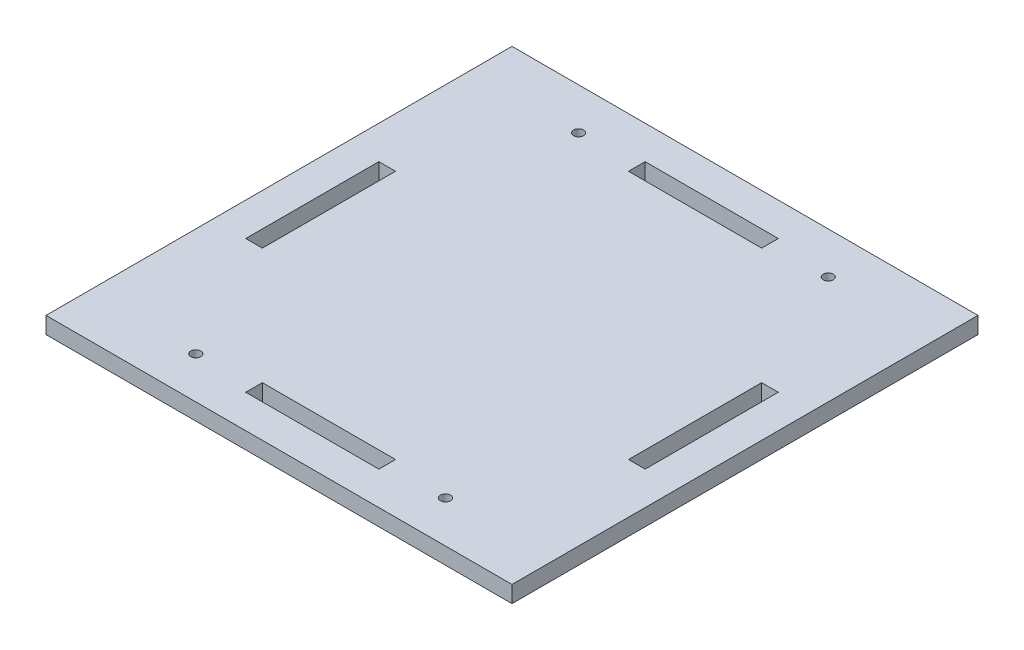
SolidWorks part; units mm, degrees
material "CA"
ref_plane "Alzado" through (0, 0, 0) normal (0, 0, 1) x (1, 0, 0)
ref_plane "Planta" through (0, 0, 0) normal (0, 1, 0) x (1, 0, 0)
ref_plane "Vista lateral" through (0, 0, 0) normal (1, 0, 0) x (0, 0, -1)
sketch "Croquis2" plane through (0, 0, 0) normal (0, 1, 0) x (1, 0, 0)
  line L0 (0, 0) -> (140, 0)
  line L1 (140, 0) -> (140, 140)
  line L2 (140, 140) -> (0, 140)
  line L3 (0, 140) -> (0, 0)
  line L4 (0, 0) -> (-1.0309, -0.8169)
  line L6 (50, 130) -> (90, 130)
  line L7 (90, 130) -> (90, 125)
  line L8 (90, 125) -> (50, 125)
  line L9 (50, 125) -> (50, 130)
  line L10 (50, 15) -> (50, 10)
  line L11 (90, 10) -> (90, 15)
  line L12 (50, 10) -> (90, 10)
  line L13 (90, 15) -> (50, 15)
  line L14 (125, 50) -> (130, 50)
  line L15 (130, 50) -> (130, 90)
  line L16 (130, 90) -> (125, 90)
  line L17 (125, 90) -> (125, 50)
  line L19 (15, 50) -> (10, 50)
  line L20 (10, 90) -> (15, 90)
  line L21 (15, 90) -> (15, 50)
  line L22 (10, 50) -> (10, 90)
  circle A2 centre (32.5, 127.5) radius 1.5
  circle A3 centre (107.5, 127.5) radius 1.5
  circle A4 centre (107.5, 12.5) radius 1.5
  circle A5 centre (32.5, 12.5) radius 1.5
  point P17 (70, 140)
  point P18 (70, 0)
  point P19 (70, 10)
  point P20 (130, 70)
  point P23 (140, 70)
  dimension "D1" = 140
  dimension "D2" = 140
  dimension "D3" = 40
  dimension "D4" = 5
  dimension "D5" = 50
  dimension "D7" = 10
  dimension "D8" = 10
  dimension "D9" = 5
  dimension "D10" = 40
  dimension "D11" = 10
extrude "Saliente-Extruir1" add sketch "Croquis2" along normal blind 5
